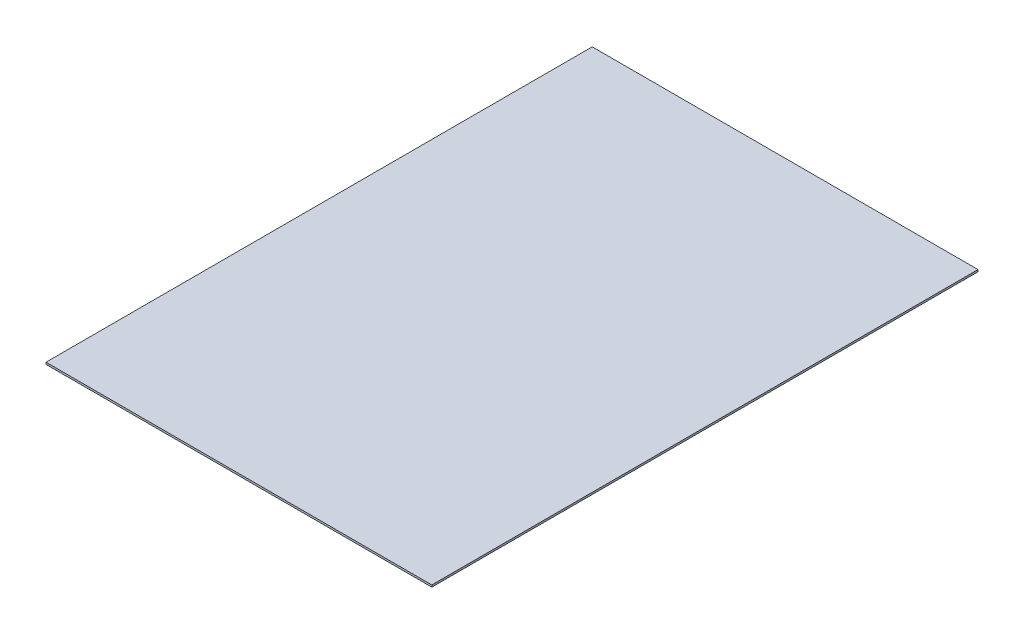
SolidWorks part; units mm, degrees
ref_plane "Front Plane" through (0, 0, 0) normal (0, 0, 1) x (1, 0, 0)
ref_plane "Top Plane" through (0, 0, 0) normal (0, 1, 0) x (1, 0, 0)
ref_plane "Right Plane" through (0, 0, 0) normal (1, 0, 0) x (0, 0, -1)
sketch "Sketch1" plane through (0, 0, 0) normal (0, 1, 0) x (1, 0, 0)
  line L1 (-297, -420.5) -> (297, -420.5)
  line L2 (-297, -420.5) -> (-297, 420.5)
  line L3 (-297, 420.5) -> (297, 420.5)
  line L4 (297, -420.5) -> (297, 420.5)
  line L5 (-297, -420.5) -> (297, 420.5) construction
  line L6 (-297, 420.5) -> (297, -420.5) construction
  point P0 (0, 0)
  dimension "D1" = 594
  dimension "D2" = 841
extrude "Boss-Extrude1" add sketch "Sketch1" along normal blind 3
